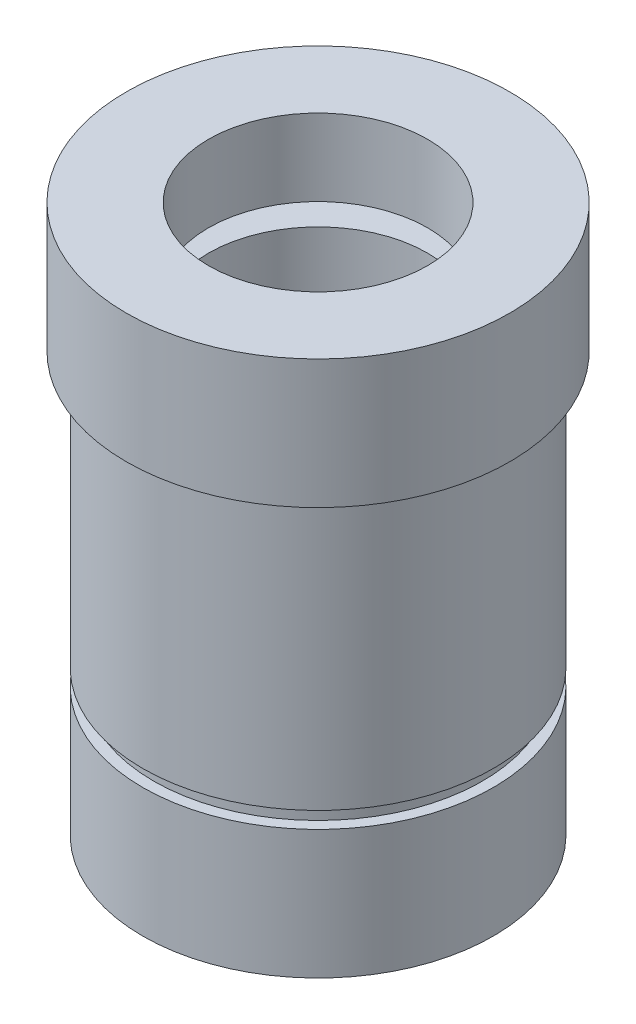
SolidWorks part; units mm, degrees
material "Beryllium S-200F, Vacuum Hot Pressed"
ref_plane "Front Plane" through (0, 0, 0) normal (0, 0, 1) x (1, 0, 0)
ref_plane "Top Plane" through (0, 0, 0) normal (0, 1, 0) x (1, 0, 0)
ref_plane "Right Plane" through (0, 0, 0) normal (1, 0, 0) x (0, 0, -1)
sketch "Sketch1" plane through (0, 0, 0) normal (0, 0, 1) x (1, 0, 0)
  line L0 (0, 23.3627) -> (0, -31.0453) construction
  line L1 (0, 23.1321) -> (17.5, 23.1321)
  line L2 (17.5, 23.1321) -> (17.5, 11.3821)
  line L3 (17.5, 11.3821) -> (16, 11.3821)
  line L4 (16, 11.3821) -> (16, -13.6179)
  line L5 (16, -13.6179) -> (15, -13.6179)
  line L6 (15, -13.6179) -> (15, -15.1179)
  line L7 (15, -15.1179) -> (16, -15.1179)
  line L8 (16, -15.1179) -> (16, -26.8679)
  line L9 (16, -26.8679) -> (0, -26.8679)
  line L10 (0, -26.8679) -> (0, 23.1321)
  dimension "D1" = 50
  dimension "D2" = 11.75
  dimension "D3" = 11.75
  dimension "D4" = 25
  dimension "D5" = 1.5
  dimension "D6" = 17.5
  dimension "D7" = 16
  dimension "D8" = 1.5
  dimension "D9" = 1
revolve "Revolve1" add sketch "Sketch1" angle 360 about L0
sketch "Sketch2" plane through (0, 23.1321, 0) normal (0, 1, 0) x (1, 0, 0)
  circle A0 centre (0, 0) radius 10
  dimension "D1" = 20
extrude "Cut-Extrude1" cut sketch "Sketch2" against normal through all
ref_plane "Plane1" through (0, 16.1321, 0) normal (0, 1, 0) x (1, 0, 0)
sketch "Sketch3" plane through (0, 16.1321, 0) normal (0, 1, 0) x (1, 0, 0)
  circle A0 centre (0, 0) radius 13
  dimension "D1" = 26
extrude "Cut-Extrude2" cut sketch "Sketch3" against normal blind 2
ref_plane "Plane2" through (0, -19.8679, 0) normal (0, -1, 0) x (-1, 0, 0)
sketch "Sketch4" plane through (0, -19.8679, 0) normal (0, -1, 0) x (-1, 0, 0)
  circle A0 centre (0, 0) radius 13
  dimension "D1" = 26
extrude "Cut-Extrude3" cut sketch "Sketch4" against normal blind 2
